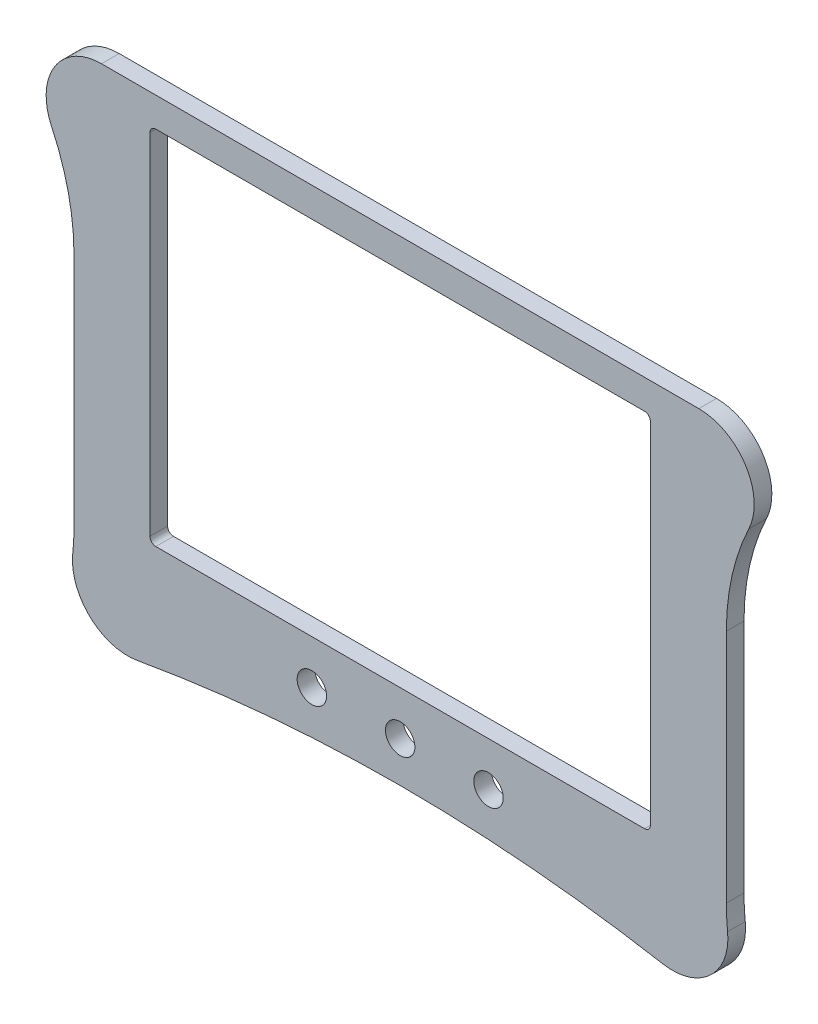
SolidWorks part; units mm, degrees
ref_plane "Front Plane" through (0, 0, 0) normal (0, 0, 1) x (1, 0, 0)
ref_plane "Top Plane" through (0, 0, 0) normal (0, 1, 0) x (1, 0, 0)
ref_plane "Right Plane" through (0, 0, 0) normal (1, 0, 0) x (0, 0, -1)
sketch "Sketch1" plane through (0, 0, 0) normal (0, 0, 1) x (1, 0, 0)
  line L0 (-58.7547, 330.8979) -> (-64.4247, 414.8138) construction
  line L1 (-64.4247, 414.8138) -> (64.4247, 414.8138) construction
  line L2 (64.4247, 414.8138) -> (58.7547, 330.8979) construction
  line L3 (58.7547, 330.8979) -> (-58.7547, 330.8979) construction
  line L4 (-120.65, 388.1438) -> (-120.65, 337.3438) construction
  line L5 (120.65, 388.1438) -> (120.65, 337.3438) construction
  line L14 (70.358, 337.3438) -> (70.358, 388.1438)
  line L15 (64.4247, 426.7518) -> (-64.4247, 426.7518)
  line L16 (-70.358, 388.1438) -> (-70.358, 337.3438)
  line L28 (71.12, 337.3438) -> (71.12, 388.1438) construction
  line L29 (-71.12, 388.1438) -> (-71.12, 337.3438) construction
  line L30 (64.4247, 427.5138) -> (-64.4247, 427.5138) construction
  arc A9 (75.2108, 409.6975) -> (70.358, 388.1438) centre (120.65, 388.1438) ccw
  arc A10 (75.2108, 409.6975) -> (64.4247, 426.7518) centre (64.4247, 414.8138) ccw
  arc A11 (-75.2108, 409.6975) -> (-64.4247, 426.7518) centre (-64.4247, 414.8138) cw
  arc A12 (-70.358, 388.1438) -> (-75.2108, 409.6975) centre (-120.65, 388.1438) ccw
  arc A13 (-70.6285, 332.1345) -> (-70.358, 337.3438) centre (-120.65, 337.3438) ccw
  arc A14 (-56.6676, 319.1438) -> (-70.6285, 332.1345) centre (-58.7547, 330.8979) cw
  arc A15 (56.6676, 319.1438) -> (-56.6676, 319.1438) centre (0, 0) ccw
  arc A16 (70.6285, 332.1345) -> (56.6676, 319.1438) centre (58.7547, 330.8979) cw
  arc A17 (70.358, 337.3438) -> (70.6285, 332.1345) centre (120.65, 337.3438) ccw
  arc A30 (-56.5344, 318.3935) -> (-71.3864, 332.2134) centre (-58.7547, 330.8979) cw construction
  arc A31 (71.3864, 332.2134) -> (56.5344, 318.3935) centre (58.7547, 330.8979) cw construction
  arc A32 (75.8993, 409.3709) -> (64.4247, 427.5138) centre (64.4247, 414.8138) ccw construction
  arc A33 (-75.8993, 409.3709) -> (-64.4247, 427.5138) centre (-64.4247, 414.8138) cw construction
  arc A40 (75.8993, 409.3709) -> (71.12, 388.1438) centre (120.65, 388.1438) ccw construction
  arc A41 (71.12, 337.3438) -> (71.3864, 332.2134) centre (120.65, 337.3438) ccw construction
  arc A42 (56.5344, 318.3935) -> (-56.5344, 318.3935) centre (0, 0) ccw construction
  arc A43 (-71.3864, 332.2134) -> (-71.12, 337.3438) centre (-120.65, 337.3438) ccw construction
  arc A44 (-71.12, 388.1438) -> (-75.8993, 409.3709) centre (-120.65, 388.1438) ccw construction
  dimension "D2" = 12.7
  dimension "D5" = 49.53
  dimension "D6" = 49.53
  dimension "D8" = 93.865
  dimension "D9" = 323.3738
  dimension "D10" = 49.53
  dimension "D1" = 83.9158
  dimension "D3" = 117.5095
  dimension "D4" = 128.8494
  dimension "D7" = 50.8
  dimension "D11" = 49.53
  dimension "D12" = 50.8
  dimension "D13" = 0.762
extrude "Boss-Extrude1" add sketch "Sketch1" along normal blind 3.81
sketch "Sketch2" plane through (0, 0, 3.81) normal (0, 0, 1) x (1, 0, 0)
  line L0 (64.4247, 426.7518) -> (-64.4247, 426.7518) construction
  line L1 (-52.705, 420.4018) -> (52.705, 420.4018)
  line L2 (-53.975, 419.1318) -> (-53.975, 343.6938)
  line L3 (-52.705, 342.4238) -> (52.705, 342.4238)
  line L4 (53.975, 419.1318) -> (53.975, 343.6938)
  line L5 (0, -1000) -> (0, 49000) construction
  line L6 (0, 332.8988) -> (-19.05, 332.8988) construction
  line L7 (0, 332.8988) -> (19.05, 332.8988) construction
  line L8 (-19.05, 336.0738) -> (19.05, 336.0738) construction
  circle A0 centre (-19.05, 332.8988) radius 3.175
  circle A1 centre (0, 332.8988) radius 3.175
  circle A2 centre (19.05, 332.8988) radius 3.175
  arc A3 (52.705, 420.4018) -> (53.975, 419.1318) centre (52.705, 419.1318) cw
  arc A4 (52.705, 342.4238) -> (53.975, 343.6938) centre (52.705, 343.6938) ccw
  arc A5 (-53.975, 343.6938) -> (-52.705, 342.4238) centre (-52.705, 343.6938) ccw
  arc A6 (-52.705, 420.4018) -> (-53.975, 419.1318) centre (-52.705, 419.1318) ccw
  point P20 (53.975, 420.4018)
  point P25 (-53.975, 342.4238)
  point P28 (-53.975, 420.4018)
  dimension "D8" = 6.35
  dimension "D9" = 1.27
  dimension "D1" = 107.95
  dimension "D2" = 77.978
  dimension "D3" = 6.35
  dimension "D4" = 53.975
  dimension "D5" = 19.05
  dimension "D6" = 19.05
  dimension "D7" = 9.525
extrude "Cut-Extrude1" cut sketch "Sketch2" against normal through all
